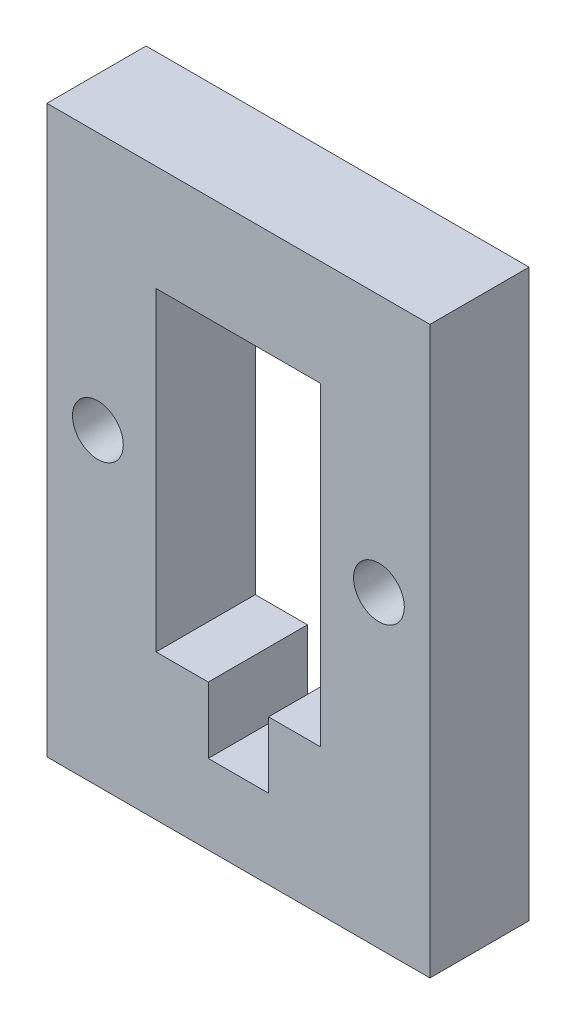
SolidWorks part; units mm, degrees
ref_plane "Front Plane" through (0, 0, 0) normal (0, 0, 1) x (1, 0, 0)
ref_plane "Top Plane" through (0, 0, 0) normal (0, 1, 0) x (1, 0, 0)
ref_plane "Right Plane" through (0, 0, 0) normal (1, 0, 0) x (0, 0, -1)
sketch "Sketch1" plane through (0, 0, 0) normal (0, 0, 1) x (1, 0, 0)
  line L1 (-18.5582, 31.0897) -> (10.4018, 31.0897)
  line L2 (-18.5582, 31.0897) -> (-18.5582, 20.0897)
  line L3 (-18.5582, 20.0897) -> (10.4018, 20.0897)
  line L4 (10.4018, 31.0897) -> (10.4018, 20.0897)
  dimension "D1" = 28.96
  dimension "D2" = 11
extrude "Boss-Extrude1" add sketch "Sketch1" along normal blind 7.5
sketch "Sketch2" plane through (0, 31.0897, 0) normal (0, 1, 0) x (1, 0, 0)
  line L0 (-18.5582, 0) -> (-10.3032, 0)
  line L1 (10.4018, 0) -> (-18.5582, 0) construction
  line L2 (-10.3032, 0) -> (-10.3032, -7.5)
  line L3 (10.4018, -7.5) -> (-18.5582, -7.5) construction
  line L4 (-10.3032, -7.5) -> (-18.5582, -7.5)
  line L5 (-18.5582, -7.5) -> (-18.5582, 0)
  line L6 (10.4018, 0) -> (2.1468, 0)
  line L7 (2.1468, 0) -> (2.1468, -7.5)
  line L8 (2.1468, -7.5) -> (10.4018, -7.5)
  line L9 (10.4018, -7.5) -> (10.4018, 0)
  dimension "D1" = 12.45
extrude "Boss-Extrude2" add sketch "Sketch2" along normal blind 23.8
sketch "Sketch3" plane through (0, 54.8897, 0) normal (0, 1, 0) x (1, 0, 0)
  line L1 (-18.5582, 0) -> (10.4018, 0)
  line L2 (-18.5582, 0) -> (-18.5582, -7.5)
  line L3 (-18.5582, -7.5) -> (10.4018, -7.5)
  line L4 (10.4018, 0) -> (10.4018, -7.5)
extrude "Boss-Extrude3" add sketch "Sketch3" along normal blind 8
sketch "Sketch4" plane through (0, 31.0897, 0) normal (0, 1, 0) x (1, 0, 0)
  line L0 (10.4018, 0) -> (-18.5582, 0) construction
  line L1 (-6.3582, 0) -> (-1.7982, 0)
  line L2 (-6.3582, 0) -> (-6.3582, -7.5)
  line L3 (-6.3582, -7.5) -> (-1.7982, -7.5)
  line L4 (-1.7982, 0) -> (-1.7982, -7.5)
  line L5 (-18.5582, -7.5) -> (10.4018, -7.5) construction
  line L6 (-18.5582, 0) -> (-18.5582, -7.5) construction
  line L7 (10.4018, -7.5) -> (10.4018, 0) construction
  dimension "D1" = 12.2
  dimension "D2" = 12.2
extrude "Cut-Extrude1" cut sketch "Sketch4" against normal blind 5
sketch "Sketch5" plane through (0, 0, 7.5) normal (0, 0, 1) x (1, 0, 0)
  line L0 (-18.5582, 62.8897) -> (10.4018, 62.8897) construction
  line L1 (-10.3032, 54.8897) -> (-10.3032, 31.0897) construction
  line L2 (2.1468, 54.8897) -> (2.1468, 31.0897) construction
  circle A0 centre (-14.7032, 43.4097) radius 1.92
  circle A1 centre (6.5468, 43.4097) radius 1.92
  dimension "D1" = 3.84
  dimension "D3" = 4.4
  dimension "D4" = 4.4
  dimension "D5" = 19.48
  dimension "D2" = 19.48
extrude "Cut-Extrude2" cut sketch "Sketch5" against normal blind 10
